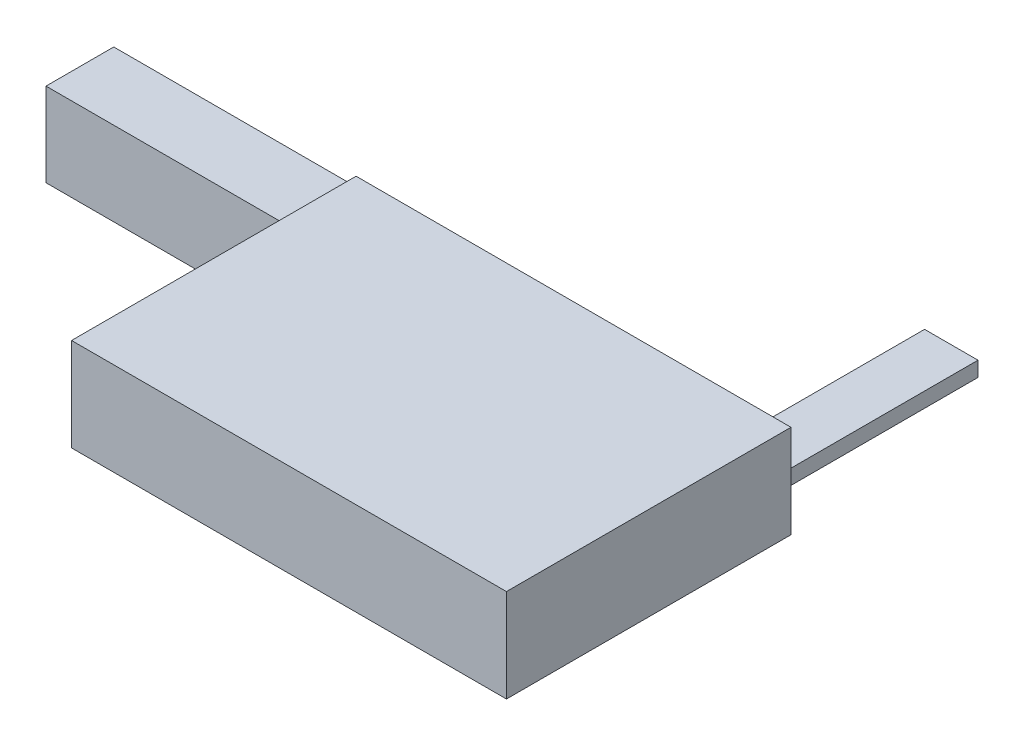
SolidWorks part; units mm, degrees
ref_plane "Спереди" through (0, 0, 0) normal (0, 0, 1) x (1, 0, 0)
ref_plane "Сверху" through (0, 0, 0) normal (0, 1, 0) x (1, 0, 0)
ref_plane "Справа" through (0, 0, 0) normal (1, 0, 0) x (0, 0, -1)
sketch "Эскиз1" plane through (0, 0, 0) normal (0, 1, 0) x (1, 0, 0)
  line L1 (-68.9663, 21.5412) -> (19.3337, 21.5412)
  line L2 (-68.9663, 21.5412) -> (-68.9663, -36.2288)
  line L3 (-68.9663, -36.2288) -> (19.3337, -36.2288)
  line L4 (19.3337, 21.5412) -> (19.3337, -36.2288)
  dimension "D1" = 88.3
  dimension "D2" = 57.77
extrude "Бобышка-Вытянуть1" add sketch "Эскиз1" along normal blind 18.9
sketch "Эскиз2" plane through (-68.9663, 0, 0) normal (-1, 0, 0) x (0, 0, 1)
  line L1 (-20.3427, 18.2228) -> (-6.5827, 18.2228)
  line L2 (-20.3427, 18.2228) -> (-20.3427, 1.2228)
  line L3 (-20.3427, 1.2228) -> (-6.5827, 1.2228)
  line L4 (-6.5827, 18.2228) -> (-6.5827, 1.2228)
  dimension "D1" = 13.76
  dimension "D2" = 17
extrude "Бобышка-Вытянуть2" add sketch "Эскиз2" along normal blind 48
sketch "Эскиз3" plane through (0, 0, -21.5412) normal (0, 0, -1) x (-1, 0, 0)
  line L1 (-12.3032, 4.6833) -> (-1.4544, 4.6833)
  line L2 (-12.3032, 4.6833) -> (-12.3032, 1.6456)
  line L3 (-12.3032, 1.6456) -> (-1.4544, 1.6456)
  line L4 (-1.4544, 4.6833) -> (-1.4544, 1.6456)
extrude "Бобышка-Вытянуть3" add sketch "Эскиз3" along normal blind 45
